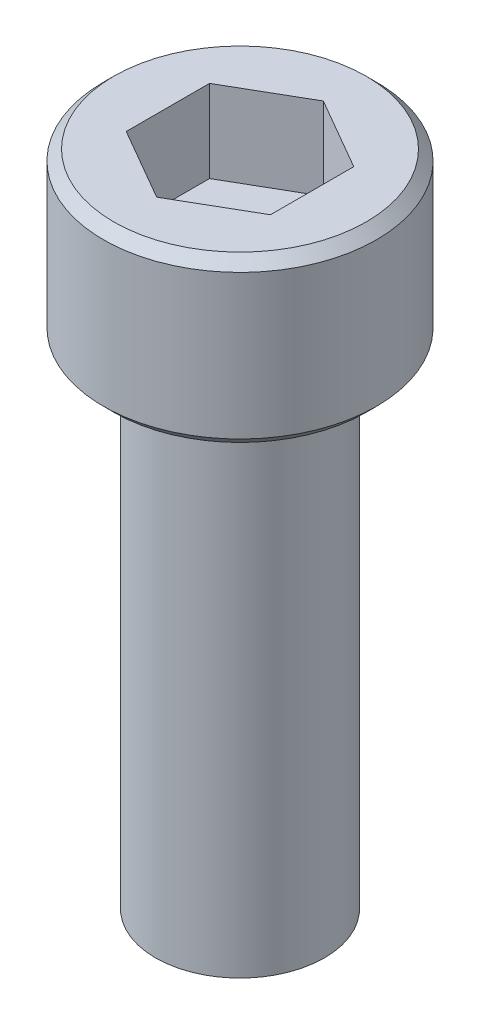
SolidWorks part; units mm, degrees
ref_plane "Front Plane" through (0, 0, 0) normal (0, 0, 1) x (1, 0, 0)
ref_plane "Top Plane" through (0, 0, 0) normal (0, 1, 0) x (1, 0, 0)
ref_plane "Right Plane" through (0, 0, 0) normal (1, 0, 0) x (0, 0, -1)
sketch "Sketch1" plane through (0, 0, 0) normal (0, 0, 1) x (1, 0, 0)
  line L0 (3.3655, 4.064) -> (0, 4.064)
  line L1 (0, 4.064) -> (0, 0)
  line L2 (0, 0) -> (3.3655, 0)
  line L3 (3.3655, 0) -> (3.3655, 4.064)
  line L4 (0, 4.064) -> (0, 0) construction
revolve "Revolve1" add sketch "Sketch1" angle 360 about L4
sketch "Sketch2" plane through (0, 0, 0) normal (0, -1, 0) x (1, 0, 0)
  circle A0 centre (0, 0) radius 2.0828
extrude "Boss-Extrude1" add sketch "Sketch2" along normal blind 12.7
sketch "Sketch3" plane through (0, 4.064, 0) normal (0, 1, 0) x (-1, 0, 0)
  line L0 (-1.778, -1.0265) -> (0, -2.0531)
  line L1 (0, -2.0531) -> (1.778, -1.0265)
  line L2 (1.778, -1.0265) -> (1.778, 1.0265)
  line L3 (1.778, 1.0265) -> (0, 2.0531)
  line L4 (0, 2.0531) -> (-1.778, 1.0265)
  line L5 (-1.778, 1.0265) -> (-1.778, -1.0265)
extrude "Cut-Extrude1" cut sketch "Sketch3" against normal blind 2.032
chamfer "Chamfer1" distance 0.254 angle 45 2 edges at (3.3655, 4.064, 0) (3.3655, 0, 0)
chamfer "Chamfer2" distance 0.7696 angle 34.979 1 edges at (2.0828, -12.7, 0)
